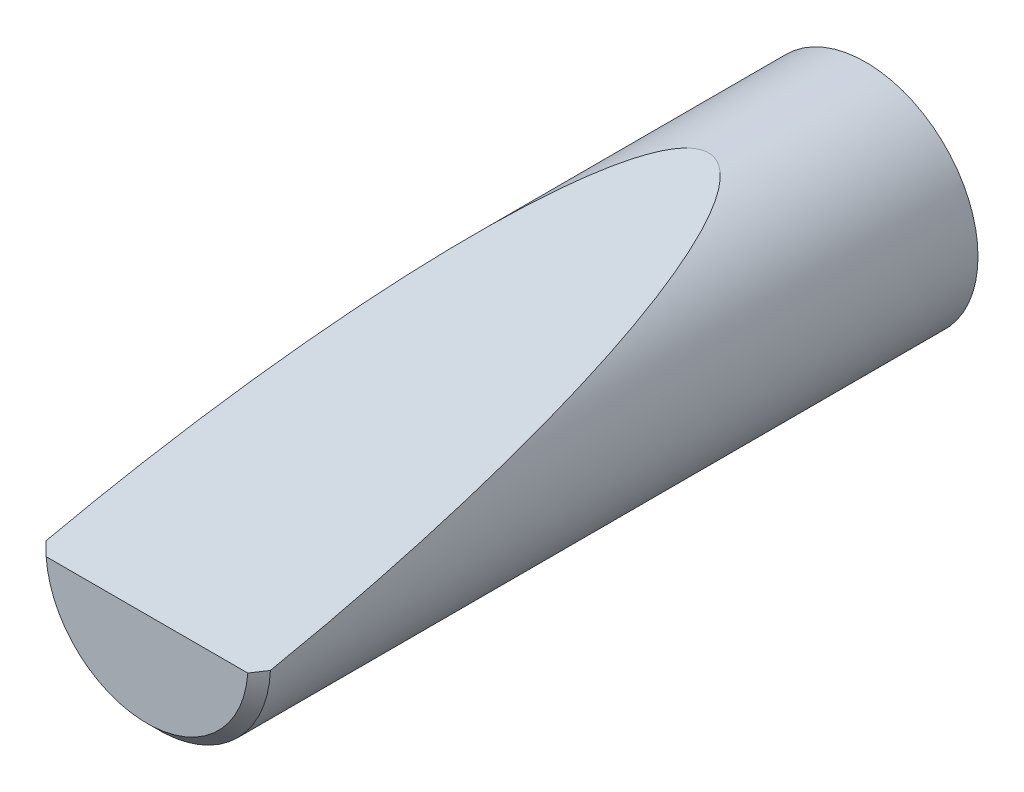
SolidWorks part; units mm, degrees
ref_plane "前视基准面" through (0, 0, 0) normal (0, 0, 1) x (1, 0, 0)
ref_plane "上视基准面" through (0, 0, 0) normal (0, 1, 0) x (1, 0, 0)
ref_plane "右视基准面" through (0, 0, 0) normal (1, 0, 0) x (0, 0, -1)
sketch "草图1" plane through (0, 0, 0) normal (0, 0, 1) x (1, 0, 0)
  circle A0 centre (0, 0) radius 10
  dimension "D1" = 20
extrude "凸台-拉伸1" add sketch "草图1" along normal blind 64
chamfer "倒角1" distance 1 angle 45 1 edges at (10, 0, 64)
sketch "草图2" plane through (0, 0, 0) normal (1, 0, 0) x (0, 0, -1)
  line L0 (-64, -0.6278) -> (-14, 10)
  line L1 (-64, 9) -> (-64, -9) construction
  line L2 (0, 10) -> (-63, 10) construction
  dimension "D1" = 50
  dimension "D2" = 12
extrude "切除-拉伸1" cut sketch "草图2" against normal through all and the other way through all
hole_wizard "Ø8.0mm 暗销孔1" positions "草图3" profile "草图4" hole size "Ø8.0" standard "GB"
sketch "草图3" plane through (0, 0, 0) normal (0, 0, -1) x (-1, 0, 0)
  point P0 (0, 0)
sketch "草图4" plane through (0, 0, 0) normal (1, 0, 0) x (0, 1, 0)
  line L0 (0, 0) -> (0, 11.5)
  line L1 (0, 11.5) -> (4, 9.1906)
  line L2 (4, 9.1906) -> (4, 2)
  line L3 (4, 2) -> (6, 0)
  line L5 (6, 0) -> (0, 0)
  line L6 (-4, 2) -> (-6, 0) construction
  line L10 (0, 11.5) -> (-4, 9.1906) construction
  line L11 (0, -6.35) -> (0, 107.95) construction
  dimension "孔直径" = 8
  dimension "孔深度" = 11.5
  dimension "近端锥形沉头孔直径" = 12
  dimension "近端锥形沉头孔角度" = 90
  dimension "导头角度" = 120
